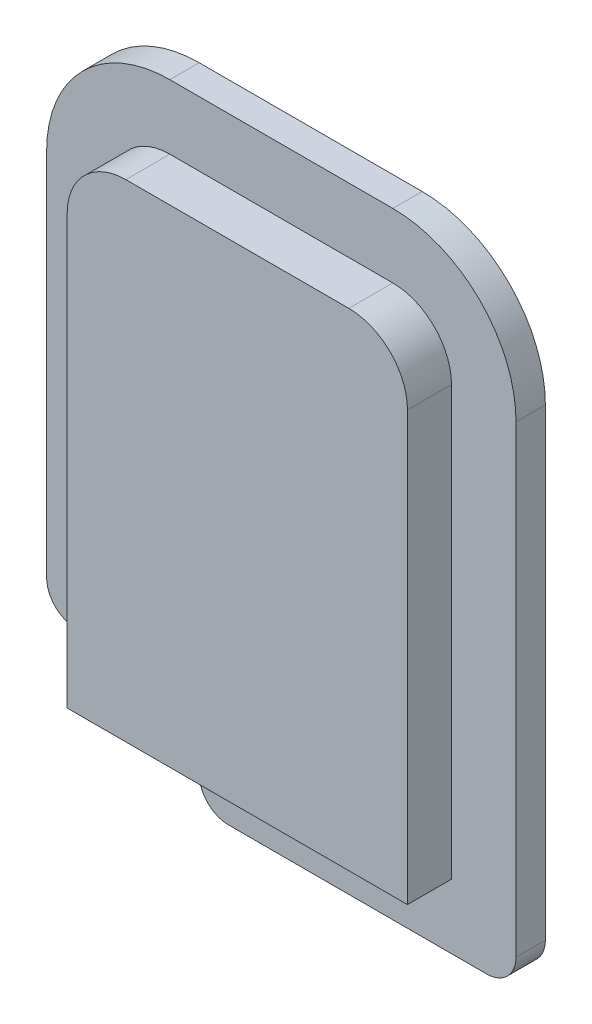
SolidWorks part; units mm, degrees
ref_plane "Front Plane" through (0, 0, 0) normal (0, 0, 1) x (1, 0, 0)
ref_plane "Top Plane" through (0, 0, 0) normal (0, 1, 0) x (1, 0, 0)
ref_plane "Right Plane" through (0, 0, 0) normal (1, 0, 0) x (0, 0, -1)
sketch "Sketch1" plane through (0, 0, 0) normal (0, 0, 1) x (1, 0, 0)
  line L1 (-5.8, 8.3) -> (5.8, 8.3)
  line L2 (-5.8, 8.3) -> (-5.8, -8.3)
  line L3 (-5.8, -8.3) -> (5.8, -8.3)
  line L4 (5.8, 8.3) -> (5.8, -8.3)
  line L5 (-5.8, 8.3) -> (5.8, -8.3) construction
  line L6 (-5.8, -8.3) -> (5.8, 8.3) construction
  point P0 (0, 0)
  dimension "D1" = 16.6
  dimension "D2" = 11.6
extrude "Boss-Extrude1" add sketch "Sketch1" along normal blind 0.3
fillet "Fillet1" radius 2 2 edges at (-5.8, 8.3, 0.15) (5.8, 8.3, 0.15)
sketch "Sketch2" plane through (0, 0, 0) normal (0, 0, -1) x (-1, 0, 0)
  line L4 (-5.8, -8.3) -> (-5.8, 6.3) construction
  line L5 (5.8, -8.3) -> (-5.8, -8.3) construction
  line L6 (5.8, 6.3) -> (5.8, -8.3) construction
  line L7 (-3.8, 8.3) -> (3.8, 8.3) construction
  line L8 (-5.8, -8.3) -> (-5.8, 6.3)
  line L9 (5.8, -8.3) -> (-5.8, -8.3)
  line L10 (5.8, 6.3) -> (5.8, -8.3)
  line L11 (-3.8, 8.3) -> (3.8, 8.3)
  line L16 (-5, -7.5) -> (-5, 6.3)
  line L17 (-3.8, 7.5) -> (3.8, 7.5)
  line L18 (5, 6.3) -> (5, -7.5)
  line L19 (5, -7.5) -> (-5, -7.5)
  arc A2 (5.8, 6.3) -> (3.8, 8.3) centre (3.8, 6.3) ccw construction
  arc A3 (-3.8, 8.3) -> (-5.8, 6.3) centre (-3.8, 6.3) ccw construction
  arc A4 (5.8, 6.3) -> (3.8, 8.3) centre (3.8, 6.3) ccw
  arc A5 (-3.8, 8.3) -> (-5.8, 6.3) centre (-3.8, 6.3) ccw
  arc A8 (-3.8, 7.5) -> (-5, 6.3) centre (-3.8, 6.3) ccw
  arc A9 (5, 6.3) -> (3.8, 7.5) centre (3.8, 6.3) ccw
  dimension "D1" = 0.8
extrude "Boss-Extrude2" add sketch "Sketch2" along normal blind 1.2
sketch "Sketch3" plane through (0, 0, -1.2) normal (0, 0, -1) x (-1, 0, 0)
  line L0 (-5, 6.3) -> (-5, -7.5) construction
  line L1 (-5, -7.5) -> (5, -7.5) construction
  line L2 (5, -7.5) -> (5, 6.3) construction
  line L3 (3.8, 7.5) -> (-3.8, 7.5) construction
  line L4 (-5, 6.3) -> (-5, -7.5)
  line L5 (-5, -7.5) -> (5, -7.5)
  line L6 (5, -7.5) -> (5, 6.3)
  line L7 (3.8, 7.5) -> (-3.8, 7.5)
  line L8 (-8, 6.3) -> (-8, -10.5)
  line L9 (-8, -10.5) -> (2.8, -10.5)
  line L10 (8, -7.3) -> (8, 6.3)
  line L11 (3.8, 10.5) -> (-3.8, 10.5)
  line L12 (5.8, -7.3) -> (8, -7.3)
  line L13 (2.8, -8.3) -> (2.8, -10.5)
  line L14 (8, -10.5) -> (8, 6.3) construction
  line L15 (-8, -10.5) -> (8, -10.5) construction
  line L16 (2.8, -8.3) -> (5.8, -8.3)
  line L17 (-5.8, -8.3) -> (5.8, -8.3) construction
  line L18 (5.8, -8.3) -> (5.8, -7.3)
  line L19 (5.8, -8.3) -> (5.8, 6.3) construction
  arc A0 (5, 6.3) -> (3.8, 7.5) centre (3.8, 6.3) ccw construction
  arc A1 (-3.8, 7.5) -> (-5, 6.3) centre (-3.8, 6.3) ccw construction
  arc A2 (5, 6.3) -> (3.8, 7.5) centre (3.8, 6.3) ccw
  arc A3 (-3.8, 7.5) -> (-5, 6.3) centre (-3.8, 6.3) ccw
  arc A4 (8, 6.3) -> (3.8, 10.5) centre (3.8, 6.3) ccw
  arc A5 (-3.8, 10.5) -> (-8, 6.3) centre (-3.8, 6.3) ccw
  dimension "D2" = 1
  dimension "D3" = 3
  dimension "D1" = 3
extrude "Boss-Extrude3" add sketch "Sketch3" along normal blind 1
fillet "Fillet2" radius 1 3 edges at (-8, -7.3, -1.7) (-2.8, -10.5, -1.7) (8, -10.5, -1.7)
